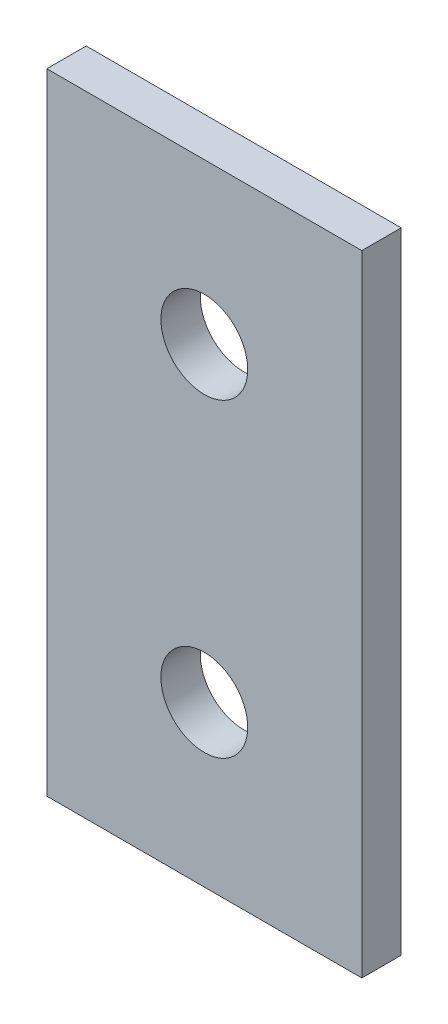
SolidWorks part; units mm, degrees
ref_plane "Front Plane" through (0, 0, 0) normal (0, 0, 1) x (1, 0, 0)
ref_plane "Top Plane" through (0, 0, 0) normal (0, 1, 0) x (1, 0, 0)
ref_plane "Right Plane" through (0, 0, 0) normal (1, 0, 0) x (0, 0, -1)
sketch "Sketch1" plane through (0, 0, 0) normal (0, 0, 1) x (1, 0, 0)
  line L0 (0, 0) -> (-50.235, 0) construction
  line L1 (-12.7, -25.4) -> (12.7, -25.4)
  line L2 (-12.7, -25.4) -> (-12.7, 25.4)
  line L3 (-12.7, 25.4) -> (12.7, 25.4)
  line L4 (12.7, -25.4) -> (12.7, 25.4)
  line L5 (-12.7, -25.4) -> (12.7, 25.4) construction
  line L6 (-12.7, 25.4) -> (12.7, -25.4) construction
  circle A0 centre (0, 12.5) radius 3.5
  circle A1 centre (0, -12.5) radius 3.5
  point P0 (0, 0)
  dimension "D4" = 7
  dimension "D1" = 25.4
  dimension "D2" = 50.8
  dimension "D3" = 12.5
extrude "Boss-Extrude1" add sketch "Sketch1" along normal blind 3.175
